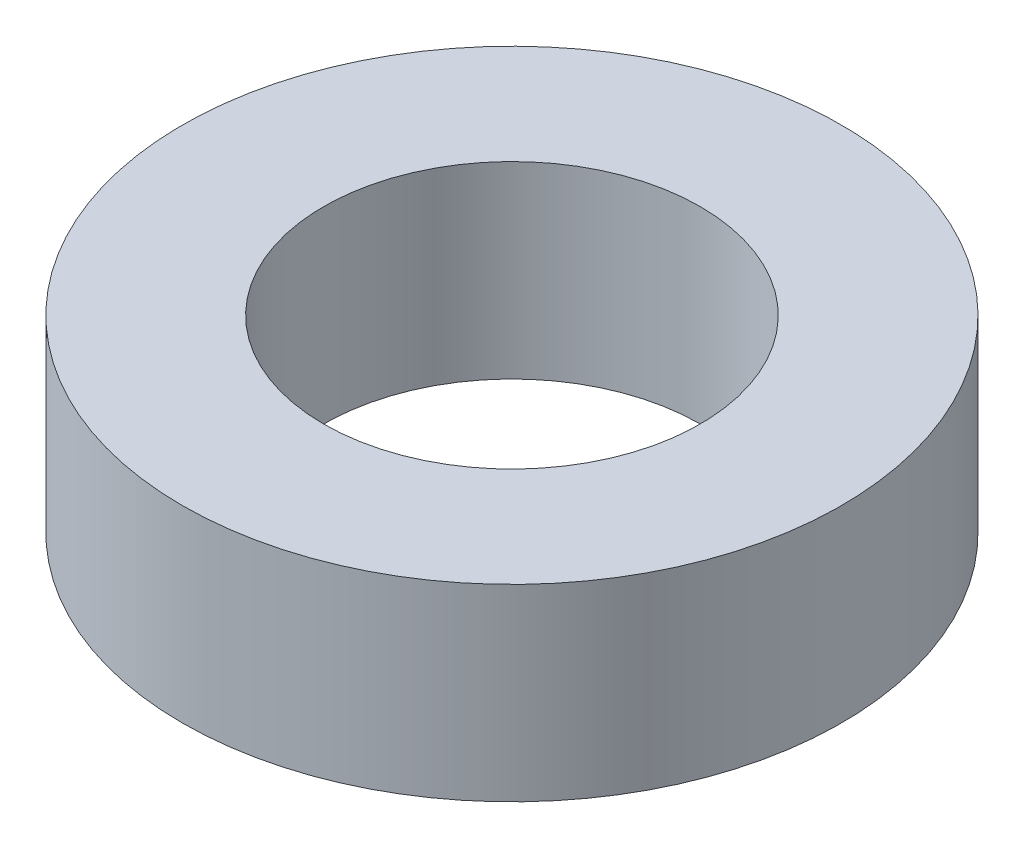
SolidWorks part; units mm, degrees
ref_plane "Front Plane" through (0, 0, 0) normal (0, 0, 1) x (1, 0, 0)
ref_plane "Top Plane" through (0, 0, 0) normal (0, 1, 0) x (1, 0, 0)
ref_plane "Right Plane" through (0, 0, 0) normal (1, 0, 0) x (0, 0, -1)
sketch "Sketch1" plane through (0, 0, 0) normal (0, 1, 0) x (1, 0, 0)
  circle A0 centre (0, 0) radius 3.5
  circle A1 centre (0, 0) radius 2
  dimension "OuterDiameter" = 7
extrude "Boss-Extrude1" add sketch "Sketch1" along normal blind 2
